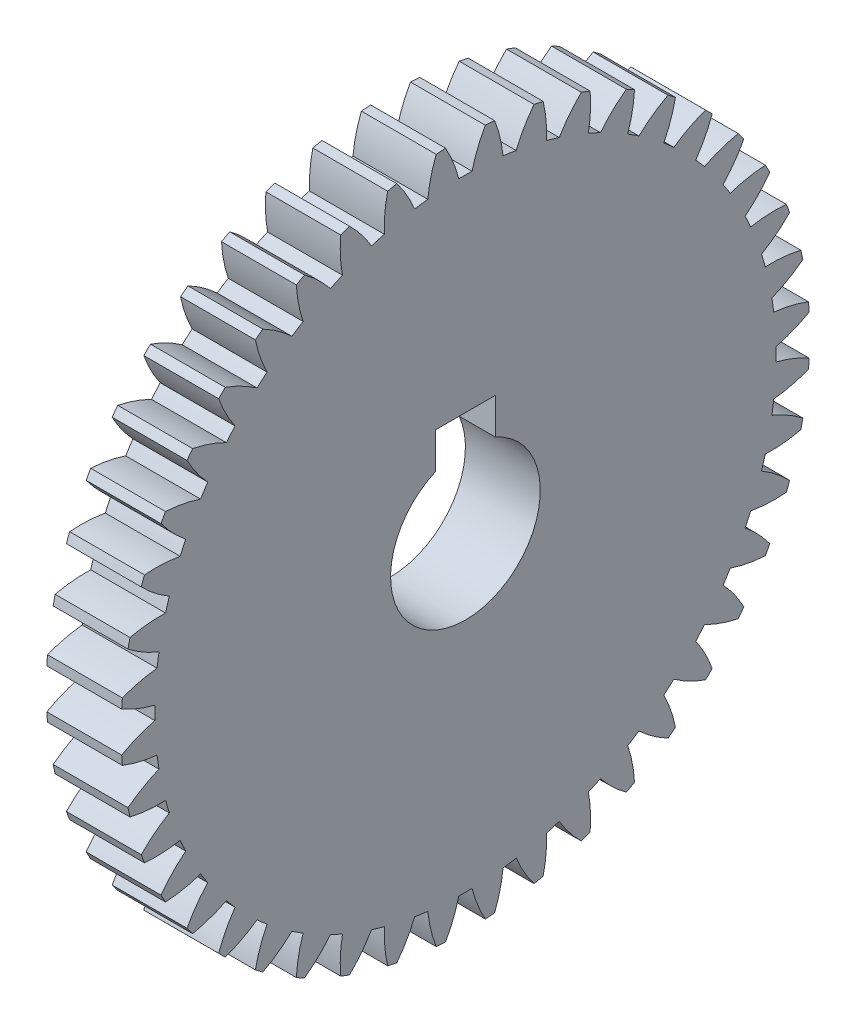
SolidWorks part; units mm, degrees
ref_plane "Alzado" through (0, 0, 0) normal (0, 0, 1) x (1, 0, 0)
ref_plane "Planta" through (0, 0, 0) normal (0, 1, 0) x (1, 0, 0)
ref_plane "Vista lateral" through (0, 0, 0) normal (1, 0, 0) x (0, 0, -1)
ref_plane "Plano1" through (5, 0, 0) normal (1, 0, 0) x (0, 0, -1)
sketch "Croquis1" plane through (5, 0, 0) normal (1, 0, 0) x (0, 0, -1)
  circle A0 centre (0, 0) radius 5
  arc A1 (3.3914, 20.47) -> (2.513, 20.5963) centre (0, 0) ccw
  arc A2 (2.513, 20.5963) -> (1.9521, 22.917) centre (-6.2421, 19.7084) ccw
  arc A3 (1.9521, 22.917) -> (1.3292, 22.9616) centre (0, 0) ccw
  arc A4 (1.3292, 22.9616) -> (0.4437, 20.7443) centre (8.9833, 18.6194) ccw
  arc A5 (0.4437, 20.7443) -> (-0.4437, 20.7443) centre (0, 0) ccw
  arc A6 (-0.4437, 20.7443) -> (-1.3292, 22.9616) centre (-8.9833, 18.6194) ccw
  arc A7 (-1.3292, 22.9616) -> (-1.9521, 22.917) centre (0, 0) ccw
  arc A8 (-1.9521, 22.917) -> (-2.513, 20.5963) centre (6.2421, 19.7084) ccw
  arc A9 (-2.513, 20.5963) -> (-3.3914, 20.47) centre (0, 0) ccw
  arc A10 (-3.3914, 20.47) -> (-4.5834, 22.5387) centre (-11.5417, 17.1514) ccw
  arc A11 (-4.5834, 22.5387) -> (-5.1937, 22.4059) centre (0, 0) ccw
  arc A12 (-5.1937, 22.4059) -> (-5.4186, 20.029) centre (3.3737, 20.3961) ccw
  arc A13 (-5.4186, 20.029) -> (-6.2701, 19.779) centre (0, 0) ccw
  arc A14 (-6.2701, 19.779) -> (-7.7444, 21.657) centre (-13.8651, 15.3343) ccw
  arc A15 (-7.7444, 21.657) -> (-8.3295, 21.4387) centre (0, 0) ccw
  arc A16 (-8.3295, 21.4387) -> (-8.2139, 19.054) centre (0.4367, 20.6686) ccw
  arc A17 (-8.2139, 19.054) -> (-9.0211, 18.6853) centre (0, 0) ccw
  arc A18 (-9.0211, 18.6853) -> (-10.7476, 20.3344) centre (-15.9063, 13.205) ccw
  arc A19 (-10.7476, 20.3344) -> (-11.2958, 20.0351) centre (0, 0) ccw
  arc A20 (-11.2958, 20.0351) -> (-10.8419, 17.6911) centre (-2.5092, 20.5204) ccw
  arc A21 (-10.8419, 17.6911) -> (-11.5885, 17.2113) centre (0, 0) ccw
  arc A22 (-11.5885, 17.2113) -> (-13.5321, 18.5979) centre (-17.6237, 10.8069) ccw
  arc A23 (-13.5321, 18.5979) -> (-14.0321, 18.2236) centre (0, 0) ccw
  arc A24 (-14.0321, 18.2236) -> (-13.2493, 15.968) centre (-5.404, 19.9544) ccw
  arc A25 (-13.2493, 15.968) -> (-13.9199, 15.3869) centre (0, 0) ccw
  arc A26 (-13.9199, 15.3869) -> (-16.0412, 16.4828) centre (-18.9823, 8.1888) ccw
  arc A27 (-16.0412, 16.4828) -> (-16.4828, 16.0412) centre (0, 0) ccw
  arc A28 (-16.4828, 16.0412) -> (-15.3869, 13.9199) centre (-8.1888, 18.9823) ccw
  arc A29 (-15.3869, 13.9199) -> (-15.968, 13.2493) centre (0, 0) ccw
  arc A30 (-15.968, 13.2493) -> (-18.2236, 14.0321) centre (-19.9544, 5.404) ccw
  arc A31 (-18.2236, 14.0321) -> (-18.5979, 13.5321) centre (0, 0) ccw
  arc A32 (-18.5979, 13.5321) -> (-17.2113, 11.5885) centre (-10.8069, 17.6237) ccw
  arc A33 (-17.2113, 11.5885) -> (-17.6911, 10.8419) centre (0, 0) ccw
  arc A34 (-17.6911, 10.8419) -> (-20.0351, 11.2958) centre (-20.5204, 2.5092) ccw
  arc A35 (-20.0351, 11.2958) -> (-20.3344, 10.7476) centre (0, 0) ccw
  arc A36 (-20.3344, 10.7476) -> (-18.6853, 9.0211) centre (-13.205, 15.9063) ccw
  arc A37 (-18.6853, 9.0211) -> (-19.054, 8.2139) centre (0, 0) ccw
  arc A38 (-19.054, 8.2139) -> (-21.4387, 8.3295) centre (-20.6686, -0.4367) ccw
  arc A39 (-21.4387, 8.3295) -> (-21.657, 7.7444) centre (0, 0) ccw
  arc A40 (-21.657, 7.7444) -> (-19.779, 6.2701) centre (-15.3343, 13.8651) ccw
  arc A41 (-19.779, 6.2701) -> (-20.029, 5.4186) centre (0, 0) ccw
  arc A42 (-20.029, 5.4186) -> (-22.4059, 5.1937) centre (-20.3961, -3.3737) ccw
  arc A43 (-22.4059, 5.1937) -> (-22.5387, 4.5834) centre (0, 0) ccw
  arc A44 (-22.5387, 4.5834) -> (-20.47, 3.3914) centre (-17.1514, 11.5417) ccw
  arc A45 (-20.47, 3.3914) -> (-20.5963, 2.513) centre (0, 0) ccw
  arc A46 (-20.5963, 2.513) -> (-22.917, 1.9521) centre (-19.7084, -6.2421) ccw
  arc A47 (-22.917, 1.9521) -> (-22.9616, 1.3292) centre (0, 0) ccw
  arc A48 (-22.9616, 1.3292) -> (-20.7443, 0.4437) centre (-18.6194, 8.9833) ccw
  arc A49 (-20.7443, 0.4437) -> (-20.7443, -0.4437) centre (0, 0) ccw
  arc A50 (-20.7443, -0.4437) -> (-22.9616, -1.3292) centre (-18.6194, -8.9833) ccw
  arc A51 (-22.9616, -1.3292) -> (-22.917, -1.9521) centre (0, 0) ccw
  arc A52 (-22.917, -1.9521) -> (-20.5963, -2.513) centre (-19.7084, 6.2421) ccw
  arc A53 (-20.5963, -2.513) -> (-20.47, -3.3914) centre (0, 0) ccw
  arc A54 (-20.47, -3.3914) -> (-22.5387, -4.5834) centre (-17.1514, -11.5417) ccw
  arc A55 (-22.5387, -4.5834) -> (-22.4059, -5.1937) centre (0, 0) ccw
  arc A56 (-22.4059, -5.1937) -> (-20.029, -5.4186) centre (-20.3961, 3.3737) ccw
  arc A57 (-20.029, -5.4186) -> (-19.779, -6.2701) centre (0, 0) ccw
  arc A58 (-19.779, -6.2701) -> (-21.657, -7.7444) centre (-15.3343, -13.8651) ccw
  arc A59 (-21.657, -7.7444) -> (-21.4387, -8.3295) centre (0, 0) ccw
  arc A60 (-21.4387, -8.3295) -> (-19.054, -8.2139) centre (-20.6686, 0.4367) ccw
  arc A61 (-19.054, -8.2139) -> (-18.6853, -9.0211) centre (0, 0) ccw
  arc A62 (-18.6853, -9.0211) -> (-20.3344, -10.7476) centre (-13.205, -15.9063) ccw
  arc A63 (-20.3344, -10.7476) -> (-20.0351, -11.2958) centre (0, 0) ccw
  arc A64 (-20.0351, -11.2958) -> (-17.6911, -10.8419) centre (-20.5204, -2.5092) ccw
  arc A65 (-17.6911, -10.8419) -> (-17.2113, -11.5885) centre (0, 0) ccw
  arc A66 (-17.2113, -11.5885) -> (-18.5979, -13.5321) centre (-10.8069, -17.6237) ccw
  arc A67 (-18.5979, -13.5321) -> (-18.2236, -14.0321) centre (0, 0) ccw
  arc A68 (-18.2236, -14.0321) -> (-15.968, -13.2493) centre (-19.9544, -5.404) ccw
  arc A69 (-15.968, -13.2493) -> (-15.3869, -13.9199) centre (0, 0) ccw
  arc A70 (-15.3869, -13.9199) -> (-16.4828, -16.0412) centre (-8.1888, -18.9823) ccw
  arc A71 (-16.4828, -16.0412) -> (-16.0412, -16.4828) centre (0, 0) ccw
  arc A72 (-16.0412, -16.4828) -> (-13.9199, -15.3869) centre (-18.9823, -8.1888) ccw
  arc A73 (-13.9199, -15.3869) -> (-13.2493, -15.968) centre (0, 0) ccw
  arc A74 (-13.2493, -15.968) -> (-14.0321, -18.2236) centre (-5.404, -19.9544) ccw
  arc A75 (-14.0321, -18.2236) -> (-13.5321, -18.5979) centre (0, 0) ccw
  arc A76 (-13.5321, -18.5979) -> (-11.5885, -17.2113) centre (-17.6237, -10.8069) ccw
  arc A77 (-11.5885, -17.2113) -> (-10.8419, -17.6911) centre (0, 0) ccw
  arc A78 (-10.8419, -17.6911) -> (-11.2958, -20.0351) centre (-2.5092, -20.5204) ccw
  arc A79 (-11.2958, -20.0351) -> (-10.7476, -20.3344) centre (0, 0) ccw
  arc A80 (-10.7476, -20.3344) -> (-9.0211, -18.6853) centre (-15.9063, -13.205) ccw
  arc A81 (-9.0211, -18.6853) -> (-8.2139, -19.054) centre (0, 0) ccw
  arc A82 (-8.2139, -19.054) -> (-8.3295, -21.4387) centre (0.4367, -20.6686) ccw
  arc A83 (-8.3295, -21.4387) -> (-7.7444, -21.657) centre (0, 0) ccw
  arc A84 (-7.7444, -21.657) -> (-6.2701, -19.779) centre (-13.8651, -15.3343) ccw
  arc A85 (-6.2701, -19.779) -> (-5.4186, -20.029) centre (0, 0) ccw
  arc A86 (-5.4186, -20.029) -> (-5.1937, -22.4059) centre (3.3737, -20.3961) ccw
  arc A87 (-5.1937, -22.4059) -> (-4.5834, -22.5387) centre (0, 0) ccw
  arc A88 (-4.5834, -22.5387) -> (-3.3914, -20.47) centre (-11.5417, -17.1514) ccw
  arc A89 (-3.3914, -20.47) -> (-2.513, -20.5963) centre (0, 0) ccw
  arc A90 (-2.513, -20.5963) -> (-1.9521, -22.917) centre (6.2421, -19.7084) ccw
  arc A91 (-1.9521, -22.917) -> (-1.3292, -22.9616) centre (0, 0) ccw
  arc A92 (-1.3292, -22.9616) -> (-0.4437, -20.7443) centre (-8.9833, -18.6194) ccw
  arc A93 (-0.4437, -20.7443) -> (0.4437, -20.7443) centre (0, 0) ccw
  arc A94 (0.4437, -20.7443) -> (1.3292, -22.9616) centre (8.9833, -18.6194) ccw
  arc A95 (1.3292, -22.9616) -> (1.9521, -22.917) centre (0, 0) ccw
  arc A96 (1.9521, -22.917) -> (2.513, -20.5963) centre (-6.2421, -19.7084) ccw
  arc A97 (2.513, -20.5963) -> (3.3914, -20.47) centre (0, 0) ccw
  arc A98 (3.3914, -20.47) -> (4.5834, -22.5387) centre (11.5417, -17.1514) ccw
  arc A99 (4.5834, -22.5387) -> (5.1937, -22.4059) centre (0, 0) ccw
  arc A100 (5.1937, -22.4059) -> (5.4186, -20.029) centre (-3.3737, -20.3961) ccw
  arc A101 (5.4186, -20.029) -> (6.2701, -19.779) centre (0, 0) ccw
  arc A102 (6.2701, -19.779) -> (7.7444, -21.657) centre (13.8651, -15.3343) ccw
  arc A103 (7.7444, -21.657) -> (8.3295, -21.4387) centre (0, 0) ccw
  arc A104 (8.3295, -21.4387) -> (8.2139, -19.054) centre (-0.4367, -20.6686) ccw
  arc A105 (8.2139, -19.054) -> (9.0211, -18.6853) centre (0, 0) ccw
  arc A106 (9.0211, -18.6853) -> (10.7476, -20.3344) centre (15.9063, -13.205) ccw
  arc A107 (10.7476, -20.3344) -> (11.2958, -20.0351) centre (0, 0) ccw
  arc A108 (11.2958, -20.0351) -> (10.8419, -17.6911) centre (2.5092, -20.5204) ccw
  arc A109 (10.8419, -17.6911) -> (11.5885, -17.2113) centre (0, 0) ccw
  arc A110 (11.5885, -17.2113) -> (13.5321, -18.5979) centre (17.6237, -10.8069) ccw
  arc A111 (13.5321, -18.5979) -> (14.0321, -18.2236) centre (0, 0) ccw
  arc A112 (14.0321, -18.2236) -> (13.2493, -15.968) centre (5.404, -19.9544) ccw
  arc A113 (13.2493, -15.968) -> (13.9199, -15.3869) centre (0, 0) ccw
  arc A114 (13.9199, -15.3869) -> (16.0412, -16.4828) centre (18.9823, -8.1888) ccw
  arc A115 (16.0412, -16.4828) -> (16.4828, -16.0412) centre (0, 0) ccw
  arc A116 (16.4828, -16.0412) -> (15.3869, -13.9199) centre (8.1888, -18.9823) ccw
  arc A117 (15.3869, -13.9199) -> (15.968, -13.2493) centre (0, 0) ccw
  arc A118 (15.968, -13.2493) -> (18.2236, -14.0321) centre (19.9544, -5.404) ccw
  arc A119 (18.2236, -14.0321) -> (18.5979, -13.5321) centre (0, 0) ccw
  arc A120 (18.5979, -13.5321) -> (17.2113, -11.5885) centre (10.8069, -17.6237) ccw
  arc A121 (17.2113, -11.5885) -> (17.6911, -10.8419) centre (0, 0) ccw
  arc A122 (17.6911, -10.8419) -> (20.0351, -11.2958) centre (20.5204, -2.5092) ccw
  arc A123 (20.0351, -11.2958) -> (20.3344, -10.7476) centre (0, 0) ccw
  arc A124 (20.3344, -10.7476) -> (18.6853, -9.0211) centre (13.205, -15.9063) ccw
  arc A125 (18.6853, -9.0211) -> (19.054, -8.2139) centre (0, 0) ccw
  arc A126 (19.054, -8.2139) -> (21.4387, -8.3295) centre (20.6686, 0.4367) ccw
  arc A127 (21.4387, -8.3295) -> (21.657, -7.7444) centre (0, 0) ccw
  arc A128 (21.657, -7.7444) -> (19.779, -6.2701) centre (15.3343, -13.8651) ccw
  arc A129 (19.779, -6.2701) -> (20.029, -5.4186) centre (0, 0) ccw
  arc A130 (20.029, -5.4186) -> (22.4059, -5.1937) centre (20.3961, 3.3737) ccw
  arc A131 (22.4059, -5.1937) -> (22.5387, -4.5834) centre (0, 0) ccw
  arc A132 (22.5387, -4.5834) -> (20.47, -3.3914) centre (17.1514, -11.5417) ccw
  arc A133 (20.47, -3.3914) -> (20.5963, -2.513) centre (0, 0) ccw
  arc A134 (20.5963, -2.513) -> (22.917, -1.9521) centre (19.7084, 6.2421) ccw
  arc A135 (22.917, -1.9521) -> (22.9616, -1.3292) centre (0, 0) ccw
  arc A136 (22.9616, -1.3292) -> (20.7443, -0.4437) centre (18.6194, -8.9833) ccw
  arc A137 (20.7443, -0.4437) -> (20.7443, 0.4437) centre (0, 0) ccw
  arc A138 (20.7443, 0.4437) -> (22.9616, 1.3292) centre (18.6194, 8.9833) ccw
  arc A139 (22.9616, 1.3292) -> (22.917, 1.9521) centre (0, 0) ccw
  arc A140 (22.917, 1.9521) -> (20.5963, 2.513) centre (19.7084, -6.2421) ccw
  arc A141 (20.5963, 2.513) -> (20.47, 3.3914) centre (0, 0) ccw
  arc A142 (20.47, 3.3914) -> (22.5387, 4.5834) centre (17.1514, 11.5417) ccw
  arc A143 (22.5387, 4.5834) -> (22.4059, 5.1937) centre (0, 0) ccw
  arc A144 (22.4059, 5.1937) -> (20.029, 5.4186) centre (20.3961, -3.3737) ccw
  arc A145 (20.029, 5.4186) -> (19.779, 6.2701) centre (0, 0) ccw
  arc A146 (19.779, 6.2701) -> (21.657, 7.7444) centre (15.3343, 13.8651) ccw
  arc A147 (21.657, 7.7444) -> (21.4387, 8.3295) centre (0, 0) ccw
  arc A148 (21.4387, 8.3295) -> (19.054, 8.2139) centre (20.6686, -0.4367) ccw
  arc A149 (19.054, 8.2139) -> (18.6853, 9.0211) centre (0, 0) ccw
  arc A150 (18.6853, 9.0211) -> (20.3344, 10.7476) centre (13.205, 15.9063) ccw
  arc A151 (20.3344, 10.7476) -> (20.0351, 11.2958) centre (0, 0) ccw
  arc A152 (20.0351, 11.2958) -> (17.6911, 10.8419) centre (20.5204, 2.5092) ccw
  arc A153 (17.6911, 10.8419) -> (17.2113, 11.5885) centre (0, 0) ccw
  arc A154 (17.2113, 11.5885) -> (18.5979, 13.5321) centre (10.8069, 17.6237) ccw
  arc A155 (18.5979, 13.5321) -> (18.2236, 14.0321) centre (0, 0) ccw
  arc A156 (18.2236, 14.0321) -> (15.968, 13.2493) centre (19.9544, 5.404) ccw
  arc A157 (15.968, 13.2493) -> (15.3869, 13.9199) centre (0, 0) ccw
  arc A158 (15.3869, 13.9199) -> (16.4828, 16.0412) centre (8.1888, 18.9823) ccw
  arc A159 (16.4828, 16.0412) -> (16.0412, 16.4828) centre (0, 0) ccw
  arc A160 (16.0412, 16.4828) -> (13.9199, 15.3869) centre (18.9823, 8.1888) ccw
  arc A161 (13.9199, 15.3869) -> (13.2493, 15.968) centre (0, 0) ccw
  arc A162 (13.2493, 15.968) -> (14.0321, 18.2236) centre (5.404, 19.9544) ccw
  arc A163 (14.0321, 18.2236) -> (13.5321, 18.5979) centre (0, 0) ccw
  arc A164 (13.5321, 18.5979) -> (11.5885, 17.2113) centre (17.6237, 10.8069) ccw
  arc A165 (11.5885, 17.2113) -> (10.8419, 17.6911) centre (0, 0) ccw
  arc A166 (10.8419, 17.6911) -> (11.2958, 20.0351) centre (2.5092, 20.5204) ccw
  arc A167 (11.2958, 20.0351) -> (10.7476, 20.3344) centre (0, 0) ccw
  arc A168 (10.7476, 20.3344) -> (9.0211, 18.6853) centre (15.9063, 13.205) ccw
  arc A169 (9.0211, 18.6853) -> (8.2139, 19.054) centre (0, 0) ccw
  arc A170 (8.2139, 19.054) -> (8.3295, 21.4387) centre (-0.4367, 20.6686) ccw
  arc A171 (8.3295, 21.4387) -> (7.7444, 21.657) centre (0, 0) ccw
  arc A172 (7.7444, 21.657) -> (6.2701, 19.779) centre (13.8651, 15.3343) ccw
  arc A173 (6.2701, 19.779) -> (5.4186, 20.029) centre (0, 0) ccw
  arc A174 (5.4186, 20.029) -> (5.1937, 22.4059) centre (-3.3737, 20.3961) ccw
  arc A175 (5.1937, 22.4059) -> (4.5834, 22.5387) centre (0, 0) ccw
  arc A176 (4.5834, 22.5387) -> (3.3914, 20.47) centre (11.5417, 17.1514) ccw
extrude "Saliente-Extruir1" add sketch "Croquis1" against normal blind 5
sketch "Croquis2" plane through (0, 0, 0) normal (-1, 0, 0) x (0, 0, 1)
  line L1 (-2, 7) -> (2, 7)
  line L2 (-2, 7) -> (-2, 4.5826)
  line L4 (2, 7) -> (2, 4.5826)
  circle A0 centre (0, 0) radius 5 construction
  arc A1 (2, 4.5826) -> (-2, 4.5826) centre (0, 0) ccw
  point P1 (0, 7)
  dimension "D1" = 7
  dimension "D2" = 4
extrude "Cortar-Extruir1" cut sketch "Croquis2" against normal through all
